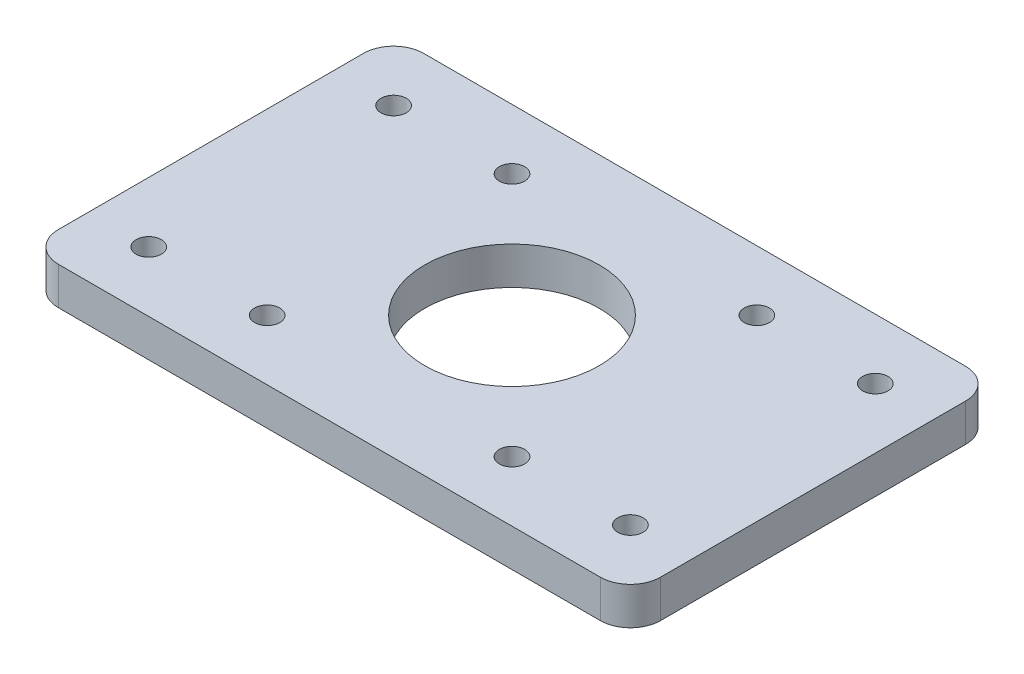
SolidWorks part; units mm, degrees
ref_plane "Front" through (0, 0, 0) normal (0, 0, 1) x (1, 0, 0)
ref_plane "Top" through (0, 0, 0) normal (0, 1, 0) x (1, 0, 0)
ref_plane "Right" through (0, 0, 0) normal (1, 0, 0) x (0, 0, -1)
sketch "Sketch1" plane through (0, 0, 0) normal (0, 1, 0) x (1, 0, 0)
  line L0 (38.1, 46.228) -> (38.1, 0) construction
  line L1 (0, 0) -> (76.2, 0)
  line L2 (0, 0) -> (0, 46.228)
  line L3 (0, 46.228) -> (76.2, 46.228)
  line L4 (76.2, 0) -> (76.2, 46.228)
  line L5 (0, 23.114) -> (76.2, 23.114) construction
  circle A0 centre (68.58, 38.608) radius 1.6
  circle A1 centre (7.62, 38.608) radius 1.6
  circle A2 centre (68.58, 7.62) radius 1.6
  circle A3 centre (7.62, 7.62) radius 1.6
  circle A4 centre (38.1, 23.114) radius 11.049
  circle A5 centre (22.606, 38.608) radius 1.6
  circle A6 centre (53.594, 38.608) radius 1.6
  circle A7 centre (22.606, 7.62) radius 1.6
  circle A8 centre (53.594, 7.62) radius 1.6
  point P23 (0, 0)
  point P24 (0, 0)
  point P29 (0, 0)
  point P30 (0, 0)
  point P31 (0, 0)
  dimension "D3" = 3.2
  dimension "D6" = 22.098
  dimension "D7" = 30.988
  dimension "D1" = 76.2
  dimension "D2" = 46.228
  dimension "D4" = 7.62
  dimension "D5" = 7.62
extrude "Boss-Extrude1" add sketch "Sketch1" along normal blind 4.7625
fillet "Fillet1" radius 3.81 4 edges at (76.2, 2.3813, -46.228) (76.2, 2.3813, 0) (0, 2.3813, 0) (0, 2.3813, -46.228)
